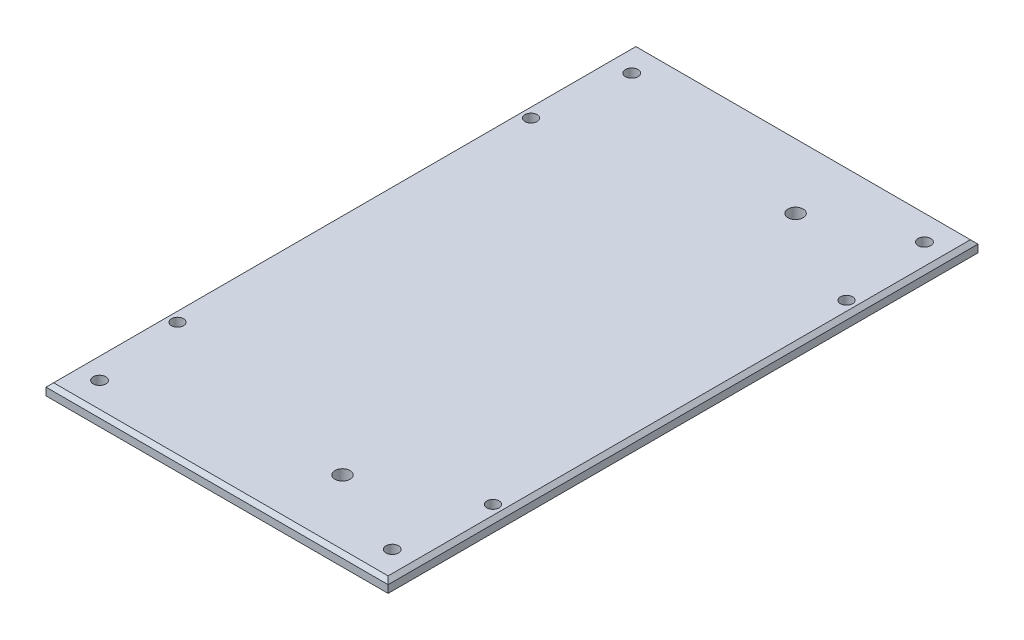
SolidWorks part; units mm, degrees
ref_plane "Front Plane" through (0, 0, 0) normal (0, 0, 1) x (1, 0, 0)
ref_plane "Top Plane" through (0, 0, 0) normal (0, 1, 0) x (1, 0, 0)
ref_plane "Right Plane" through (0, 0, 0) normal (1, 0, 0) x (0, 0, -1)
sketch "Sketch1" plane through (0, 0, 0) normal (0, 1, 0) x (1, 0, 0)
  line L0 (-45, 77.5862) -> (-45, -77.5862)
  line L1 (-45, -77.5862) -> (45, -77.5862)
  line L2 (45, -77.5862) -> (45, 77.5862)
  line L3 (45, 77.5862) -> (-45, 77.5862)
  circle A0 centre (38.5, -70) radius 1.6552
  circle A1 centre (-38.5, -70) radius 1.6552
  circle A2 centre (38.5, 70) radius 1.6552
  circle A3 centre (-38.5, 70) radius 1.6552
  point P12 (0, 77.5862)
  point P14 (45, 0)
  dimension "D3" = 77
  dimension "D4" = 140
  dimension "D5" = 70
  dimension "D6" = 38.5
  dimension "D1" = 45
  dimension "D2" = 45
extrude "Boss-Extrude1" add sketch "Sketch1" along normal blind 3
sketch "Sketch2" plane through (0, 3, 0) normal (0, 1, 0) x (1, 0, 0)
  line L5 (-41.5, -46.5) -> (41.5, -46.5)
  line L6 (-41.5, -46.5) -> (-41.5, 46.5)
  line L7 (-41.5, 46.5) -> (41.5, 46.5)
  line L8 (41.5, -46.5) -> (41.5, 46.5)
  line L9 (-41.5, -46.5) -> (41.5, 46.5) construction
  line L10 (-41.5, 46.5) -> (41.5, -46.5) construction
  circle A0 centre (-41.5, 46.5) radius 1.6
  circle A1 centre (41.5, 46.5) radius 1.6
  circle A3 centre (-41.5, -46.5) radius 1.6
  circle A4 centre (41.5, -46.5) radius 1.6
  point P0 (0, 0)
  dimension "D3" = 3.2
  dimension "D1" = 93
  dimension "D2" = 83
extrude "Cut-Extrude1" cut sketch "Sketch2" against normal through all contours L7 A0 L6 | L6 A0 L7 | L7 A1 L8 | L8 A1 L7 | L8 A4 L5 | L5 A4 L8 | L6 A3 L5 | L5 A3 L6
sketch "Sketch5" plane through (0, 3, 0) normal (0, 1, 0) x (1, 0, 0)
  circle A0 centre (-38.5, 70) radius 3
  circle A1 centre (38.5, 70) radius 3
  circle A2 centre (38.5, -70) radius 3
  circle A3 centre (-38.5, -70) radius 3
  dimension "D1" = 6
chamfer "Chamfer1" distance 1 angle 45 2 edges at (0, 3, 77.5862) (0, 3, -77.5862)
chamfer "Chamfer2" distance 1 angle 45 2 edges at (45, 3, 0) (-45, 3, 0)
sketch "Sketch6" plane through (0, 3, 0) normal (0, 1, 0) x (1, 0, 0)
  line L0 (45, 77.5862) -> (45, -77.5862) construction
  line L1 (45, -77.5862) -> (-45, -77.5862) construction
  line L2 (-44, 0) -> (45, 0) construction
  line L3 (-44, 76.5862) -> (-44, -76.5862) construction
  circle A0 centre (15, -59.5862) radius 2
  circle A1 centre (15, 59.5862) radius 2
  dimension "D1" = 4
  dimension "D2" = 30
  dimension "D3" = 18
extrude "Cut-Extrude2" cut sketch "Sketch6" against normal up to surface (3 mm away) up to face at (-41.5, 0, 48.1)
